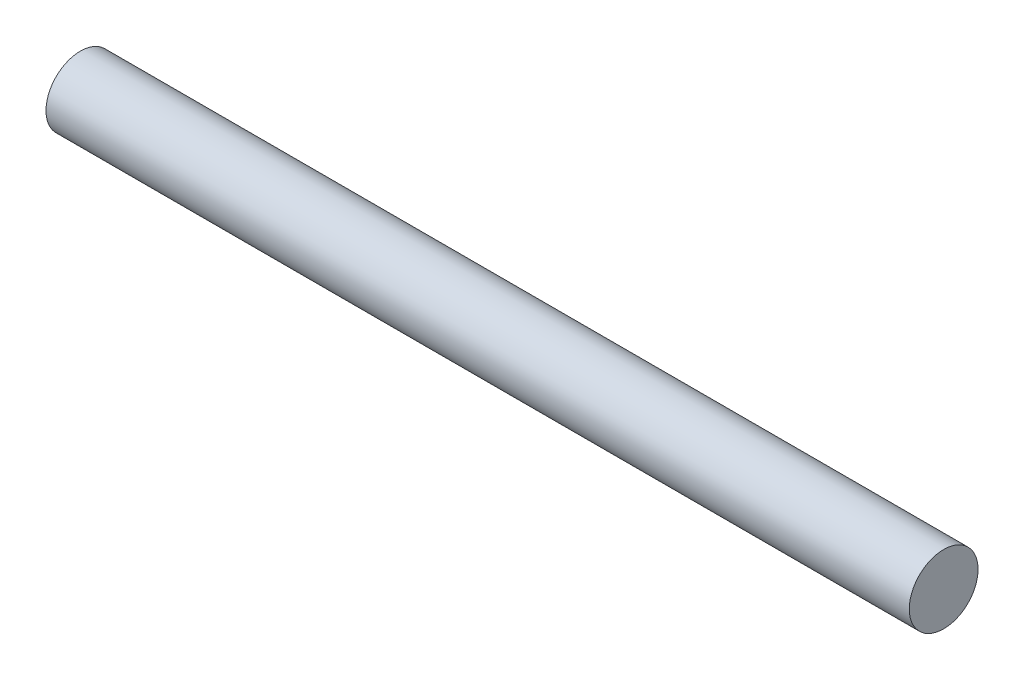
SolidWorks part; units mm, degrees
ref_plane "Front Plane" through (0, 0, 0) normal (0, 0, 1) x (1, 0, 0)
ref_plane "Top Plane" through (0, 0, 0) normal (0, 1, 0) x (1, 0, 0)
ref_plane "Right Plane" through (0, 0, 0) normal (1, 0, 0) x (0, 0, -1)
sketch "Sketch2" plane through (0, 0, 0) normal (0, 1, 0) x (1, 0, 0)
  line L0 (0, 0) -> (1600, 0)
  line L1 (1600, 0) -> (1600, 63.75)
  line L2 (1600, 63.75) -> (0, 63.75)
  line L3 (0, 63.75) -> (0, 0)
revolve "Revolve1" add sketch "Sketch2" angle 360 about L2
